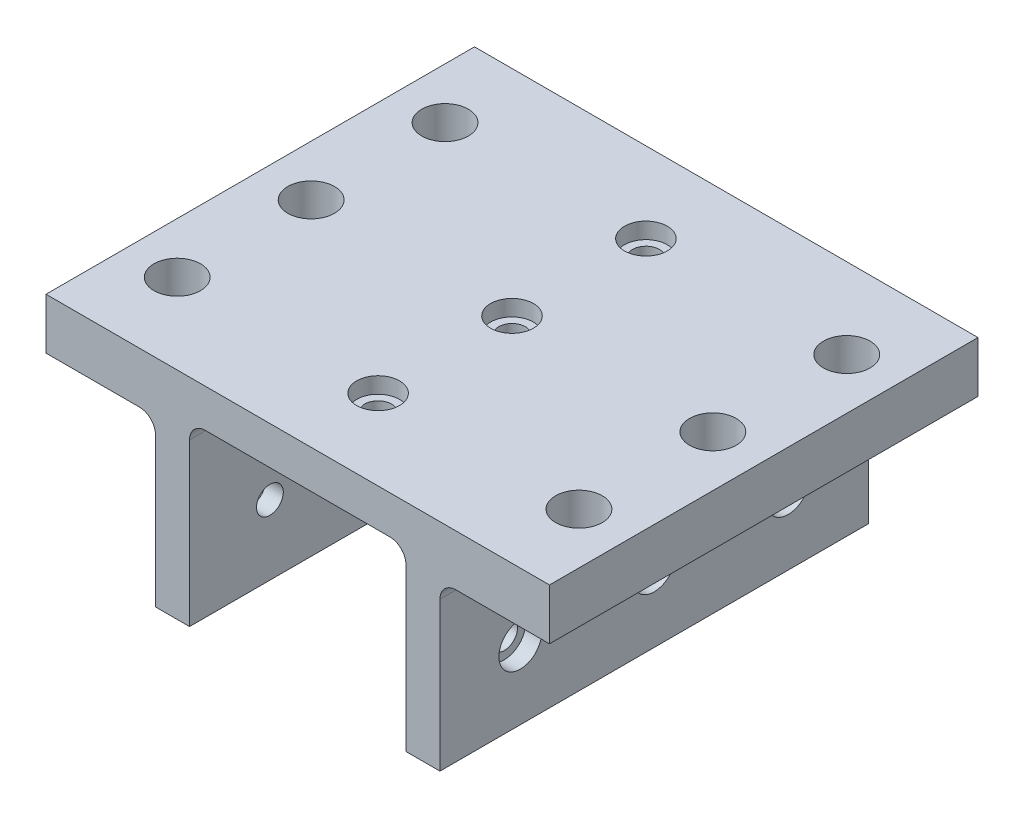
SolidWorks part; units mm, degrees
material "6061 Alloy"
ref_plane "Front Plane" through (0, 0, 0) normal (0, 0, 1) x (1, 0, 0)
ref_plane "Top Plane" through (0, 0, 0) normal (0, 1, 0) x (1, 0, 0)
ref_plane "Right Plane" through (0, 0, 0) normal (1, 0, 0) x (0, 0, -1)
sketch "Sketch2" plane through (0, 0, 0) normal (0, 0, 1) x (1, 0, 0)
  line L0 (59.4222, 153.6369) -> (153.4222, 153.6369)
  line L1 (126.6222, 113.2999) -> (132.9722, 113.2999)
  line L2 (59.4222, 144.1119) -> (76.8722, 144.1119)
  line L3 (59.4222, 144.1119) -> (59.4222, 153.6369)
  line L4 (126.6222, 138.3499) -> (126.6222, 113.2499)
  line L5 (86.2222, 113.2499) -> (86.2222, 138.3499)
  line L6 (79.8722, 113.2999) -> (79.8722, 141.1119)
  line L7 (86.2222, 113.2999) -> (86.2222, 143.4999)
  line L8 (126.6222, 113.2999) -> (126.6222, 143.4999)
  line L9 (79.8722, 113.2999) -> (86.2222, 113.2999)
  line L10 (94.3722, 146.4999) -> (118.4722, 146.4999)
  line L11 (89.2222, 146.4999) -> (123.6222, 146.4999)
  line L12 (132.9722, 113.2999) -> (132.9722, 141.1119)
  line L13 (135.9722, 144.1119) -> (153.4222, 144.1119)
  line L14 (153.4222, 144.1119) -> (153.4222, 153.6369)
  arc A0 (79.8722, 141.1119) -> (76.8722, 144.1119) centre (76.8722, 141.1119) ccw
  arc A1 (89.2222, 146.4999) -> (86.2222, 143.4999) centre (89.2222, 143.4999) ccw
  arc A2 (126.6222, 143.4999) -> (123.6222, 146.4999) centre (123.6222, 143.4999) ccw
  arc A3 (135.9722, 144.1119) -> (132.9722, 141.1119) centre (135.9722, 141.1119) ccw
extrude "Extrude1" add sketch "Sketch2" along normal blind 80 contours A3 L13 L14 L0 L3 L2 A0 L6 L9 L5 L7 A1 L11 L10 A2 L8 L4 L1 L12
sketch "Sketch3" plane through (0, 153.6369, 0) normal (0, 1, 0) x (-1, 0, 0)
  line L0 (-59.4222, 80) -> (-153.4222, 80) construction
  line L1 (-59.4222, 80) -> (-59.4222, 0) construction
  line L2 (-68.9222, 65) -> (-68.9222, 4.8475) construction
  line L4 (-106.4222, 80) -> (-106.4222, 0) construction
  line L5 (-59.4222, 0) -> (-153.4222, 0) construction
  point P0 (-68.9222, 65)
  point P1 (-68.9222, 40)
  point P2 (-68.9222, 15)
  point P13 (-143.9222, 15)
  point P14 (-143.9222, 40)
  point P16 (-143.9222, 65)
  point P17 (-106.4222, 65)
  point P18 (-106.4222, 40)
  point P19 (-106.4222, 15)
  dimension "D1" = 15
  dimension "D2" = 9.5
  dimension "D3" = 25
  dimension "D4" = 25
hole_wizard "M8.7 (8.7) Diameter Hole1" positions "3DSketch1" profile "Sketch4" hole size "M8.7" standard "DIN" end condition through all
sketch3d "3DSketch1"
  point P0 (68.9222, 153.6369, 65)
  point P2 (68.9222, 153.6369, 40)
  point P4 (68.9222, 153.6369, 15)
  point P6 (143.9222, 153.6369, 15)
  point P8 (143.9222, 153.6369, 40)
  point P10 (143.9222, 153.6369, 65)
sketch "Sketch4" plane through (68.9222, 153.6369, 65) normal (1, 0, 0) x (0, 0, 1)
  line L0 (0, 0) -> (0, 40.337)
  line L1 (0, 40.337) -> (4.35, 40.337)
  line L2 (4.35, 40.337) -> (4.35, 0)
  line L5 (4.35, 0) -> (0, 0)
  line L11 (0, -6.35) -> (0, 107.95) construction
  dimension "Thru Hole Dia." = 8.7
  dimension "Thru Hole Depth" = 40.337
hole_wizard "Hole1" positions "3DSketch2" profile "Sketch5" legacy end condition through all
sketch3d "3DSketch2"
  point P0 (106.4222, 153.6369, 65)
  point P2 (106.4222, 153.6369, 40)
  point P4 (106.4222, 153.6369, 15)
sketch "Sketch5" plane through (106.4222, 153.6369, 65) normal (1, 0, 0) x (0, 0, 1)
  line L0 (0, 0) -> (0, 40.337)
  line L1 (0, 40.337) -> (2.5, 40.337)
  line L2 (2.5, 40.337) -> (2.5, 3)
  line L3 (2.5, 3) -> (4, 3)
  line L4 (4, 3) -> (4, 0)
  line L5 (4, 0) -> (0, 0)
  line L6 (0, 110) -> (0, -10) construction
  dimension "Diameter" = 5
  dimension "Depth" = 40.337
  dimension "C-Bore Diameter" = 8
  dimension "C-Bore Depth" = 3
sketch "Sketch6" plane through (132.9722, 0, 0) normal (1, 0, 0) x (0, 0, -1)
  line L0 (-80, 153.6369) -> (0, 153.6369) construction
  line L1 (-80, 113.2999) -> (-80, 141.1119) construction
  line L2 (-65, 126.2969) -> (-8.0106, 126.2969) construction
  point P0 (-65, 126.2969)
  point P7 (-40, 126.2969)
  point P8 (-15, 126.2969)
  dimension "D1" = 27.34
  dimension "D2" = 15
  dimension "D3" = 25
  dimension "D4" = 25
hole_wizard "Hole2" positions "3DSketch3" profile "Sketch7" legacy
sketch3d "3DSketch3"
  point P0 (132.9722, 126.2969, 65)
  point P2 (132.9722, 126.2969, 40)
  point P4 (132.9722, 126.2969, 15)
sketch "Sketch7" plane through (132.9722, 126.2969, 65) normal (0, 1, 0) x (0, 0, -1)
  line L0 (0, 0) -> (0, 7)
  line L1 (0, 7) -> (2.5, 7)
  line L2 (2.5, 7) -> (2.5, 3)
  line L3 (2.5, 3) -> (4, 3)
  line L4 (4, 3) -> (4, 0)
  line L5 (4, 0) -> (0, 0)
  line L6 (0, 110) -> (0, -10) construction
  dimension "Diameter" = 5
  dimension "Depth" = 7
  dimension "C-Bore Diameter" = 8
  dimension "C-Bore Depth" = 3
ref_plane "MirrorPlane" through (106.4222, 0, 0) normal (-1, 0, 0) x (0, 0, 1)
mirror "Mirror1" about plane through (106.4222, 0, 0) normal (-1, 0, 0) of "Hole2"
